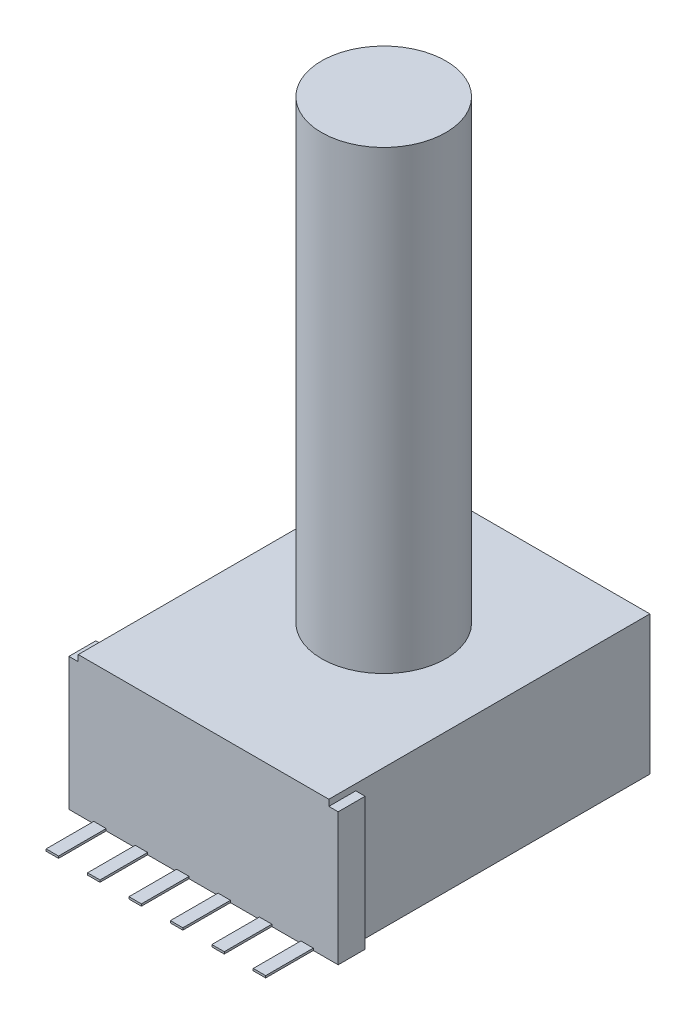
SolidWorks part; units mm, degrees
ref_plane "Front Plane" through (0, 0, 0) normal (0, 0, 1) x (1, 0, 0)
ref_plane "Top Plane" through (0, 0, 0) normal (0, 1, 0) x (1, 0, 0)
ref_plane "Right Plane" through (0, 0, 0) normal (1, 0, 0) x (0, 0, -1)
sketch "Sketch1" plane through (0, 0, 0) normal (0, 1, 0) x (1, 0, 0)
  line L0 (0, 0) -> (0, 6.8) construction
  line L1 (-6.05, 6.8) -> (6.05, 6.8)
  line L2 (-6.05, 6.8) -> (-6.05, -8.7)
  line L3 (-6.05, -8.7) -> (6.05, -8.7)
  line L4 (6.05, 6.8) -> (6.05, -8.7)
  dimension "D3" = 8.7
  dimension "D1" = 12.1
  dimension "D2" = 6.8
extrude "Extrude1" add sketch "Sketch1" along normal blind 6.7
sketch "Sketch5" plane through (0, 0, 0) normal (0, 1, 0) x (1, 0, 0)
  line L0 (-6.05, -8.7) -> (6.05, -8.7) construction
  line L1 (-6.5, -8.7) -> (6.5, -8.7)
  line L2 (-6.5, -8.7) -> (-6.5, -7.4)
  line L3 (-6.5, -7.4) -> (6.5, -7.4)
  line L4 (6.5, -8.7) -> (6.5, -7.4)
  line L5 (0, 0) -> (0, -8.7) construction
  dimension "D1" = 13
  dimension "D2" = 1.3
extrude "Extrude5" add sketch "Sketch5" along normal blind 6.4
sketch "Sketch6" plane through (0, 0, 0) normal (0, 1, 0) x (1, 0, 0)
  line L0 (0, 0) -> (0, -8.7) construction
  line L1 (-6.05, -8.7) -> (6.05, -8.7) construction
  line L2 (-5, -8.7) -> (-5, -11) construction
  line L3 (-1.3, -8.7) -> (-0.7, -8.7)
  line L4 (-1.3, -8.7) -> (-1.3, -11)
  line L5 (-1.3, -11) -> (-0.7, -11)
  line L6 (-0.7, -8.7) -> (-0.7, -11)
  line L7 (-2.7, -8.7) -> (-3.3, -8.7)
  line L8 (-2.7, -8.7) -> (-2.7, -11)
  line L9 (-2.7, -11) -> (-3.3, -11)
  line L10 (-3.3, -8.7) -> (-3.3, -11)
  line L11 (-4.7, -8.7) -> (-5.3, -8.7)
  line L12 (-4.7, -8.7) -> (-4.7, -11)
  line L13 (-4.7, -11) -> (-5.3, -11)
  line L14 (-5.3, -8.7) -> (-5.3, -11)
  line L15 (-3, -8.7) -> (-3, -11) construction
  line L16 (-1, -8.7) -> (-1, -11) construction
  line L17 (1, -8.7) -> (1, -11) construction
  line L18 (3, -8.7) -> (3, -11) construction
  line L19 (5, -8.7) -> (5, -11) construction
  line L20 (5.3, -8.7) -> (5.3, -11)
  line L21 (4.7, -11) -> (5.3, -11)
  line L22 (4.7, -8.7) -> (4.7, -11)
  line L23 (4.7, -8.7) -> (5.3, -8.7)
  line L24 (3.3, -8.7) -> (3.3, -11)
  line L25 (2.7, -11) -> (3.3, -11)
  line L26 (2.7, -8.7) -> (2.7, -11)
  line L27 (2.7, -8.7) -> (3.3, -8.7)
  line L28 (0.7, -8.7) -> (0.7, -11)
  line L29 (1.3, -11) -> (0.7, -11)
  line L30 (1.3, -8.7) -> (1.3, -11)
  line L31 (1.3, -8.7) -> (0.7, -8.7)
  dimension "D1" = 11
  dimension "D2" = 0.6
  dimension "D3" = 0.6
  dimension "D4" = 0.6
  dimension "D5" = 2
  dimension "D6" = 2
  dimension "D7" = 1
extrude "Extrude6" add sketch "Sketch6" along normal blind 0.1
sketch "Sketch7" plane through (0, 6.7, 0) normal (0, 1, 0) x (1, 0, 0)
  circle A0 centre (0, 0) radius 3
  dimension "D1" = 6
extrude "Extrude7" add sketch "Sketch7" along normal blind 22
